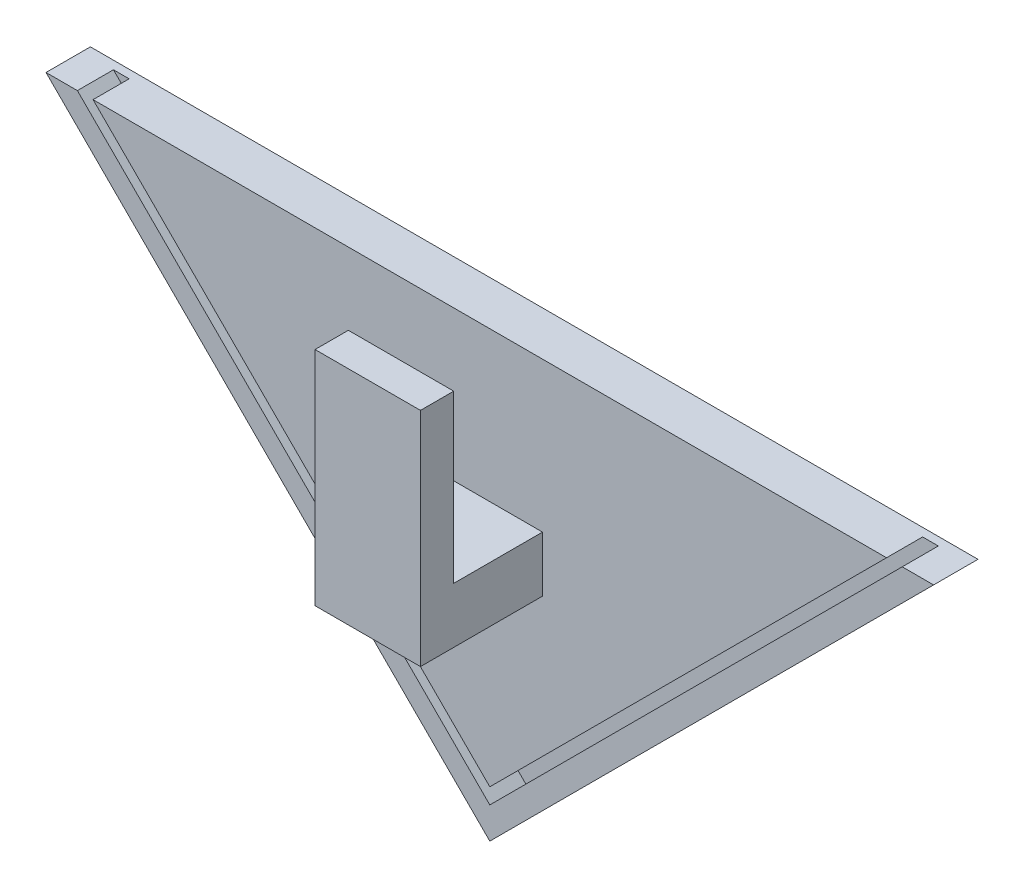
SolidWorks part; units mm, degrees
ref_plane "Front Plane" through (0, 0, 0) normal (0, 0, 1) x (1, 0, 0)
ref_plane "Top Plane" through (0, 0, 0) normal (0, 1, 0) x (1, 0, 0)
ref_plane "Right Plane" through (0, 0, 0) normal (1, 0, 0) x (0, 0, -1)
sketch "Sketch1" plane through (0, 0, 0) normal (0, 0, 1) x (1, 0, 0)
  line L0 (0, 0) -> (40, 40)
  line L1 (40, 40) -> (-40, 40)
  line L2 (-40, 40) -> (0, 0)
  line L3 (0, 0) -> (0, 40) construction
  dimension "D1" = 56.5685
  dimension "D2" = 90
extrude "Boss-Extrude1" add sketch "Sketch1" along normal blind 4 contours L1 L2 L0
sketch "Sketch2" plane through (0, 0, 4) normal (0, 0, 1) x (1, 0, 0)
  line L0 (0, 2.8284) -> (-37.1716, 40)
  line L1 (40, 40) -> (-40, 40) construction
  line L3 (37.1716, 40) -> (0, 2.8284)
  line L4 (-40, 40) -> (0, 0) construction
  line L5 (0, 0) -> (0, 40) construction
  line L7 (35.7574, 40) -> (0, 4.2426)
  line L8 (0, 4.2426) -> (-35.7574, 40)
  line L9 (-37.1716, 40) -> (-35.7574, 40)
  line L10 (37.1716, 40) -> (35.7574, 40)
  line L11 (0, 4.2426) -> (-36.4645, 40.7071) construction
  line L12 (36.4645, 40.7071) -> (0, 4.2426) construction
  dimension "D1" = 2
  dimension "D2" = 1
extrude "Cut-Extrude2" cut sketch "Sketch2" against normal blind 3.25
sketch "Sketch5" plane through (0, 0, 4) normal (0, 0, 1) x (1, 0, 0)
  line L0 (0, 0) -> (0, 40) construction
  line L1 (-4.75, 21.5) -> (4.75, 21.5)
  line L2 (-4.75, 21.5) -> (-4.75, 26.5)
  line L3 (-4.75, 26.5) -> (4.75, 26.5)
  line L4 (4.75, 21.5) -> (4.75, 26.5)
  line L5 (-4.75, 21.5) -> (4.75, 26.5) construction
  line L6 (-4.75, 26.5) -> (4.75, 21.5) construction
  line L7 (40, 40) -> (-40, 40) construction
  point P0 (0, 24)
  dimension "D1" = 9.5
  dimension "D2" = 5
  dimension "D3" = 13.5
extrude "Boss-Extrude2" add sketch "Sketch5" along normal blind 8
sketch "Sketch6" plane through (0, 0, 12) normal (0, 0, 1) x (1, 0, 0)
  line L0 (4.75, 21.5) -> (4.75, 26.5) construction
  line L1 (-4.75, 21.5) -> (4.75, 21.5)
  line L2 (-4.75, 21.5) -> (-4.75, 41.5)
  line L3 (-4.75, 41.5) -> (4.75, 41.5)
  line L4 (4.75, 21.5) -> (4.75, 41.5)
  dimension "D1" = 20
extrude "Boss-Extrude3" add sketch "Sketch6" along normal blind 3
